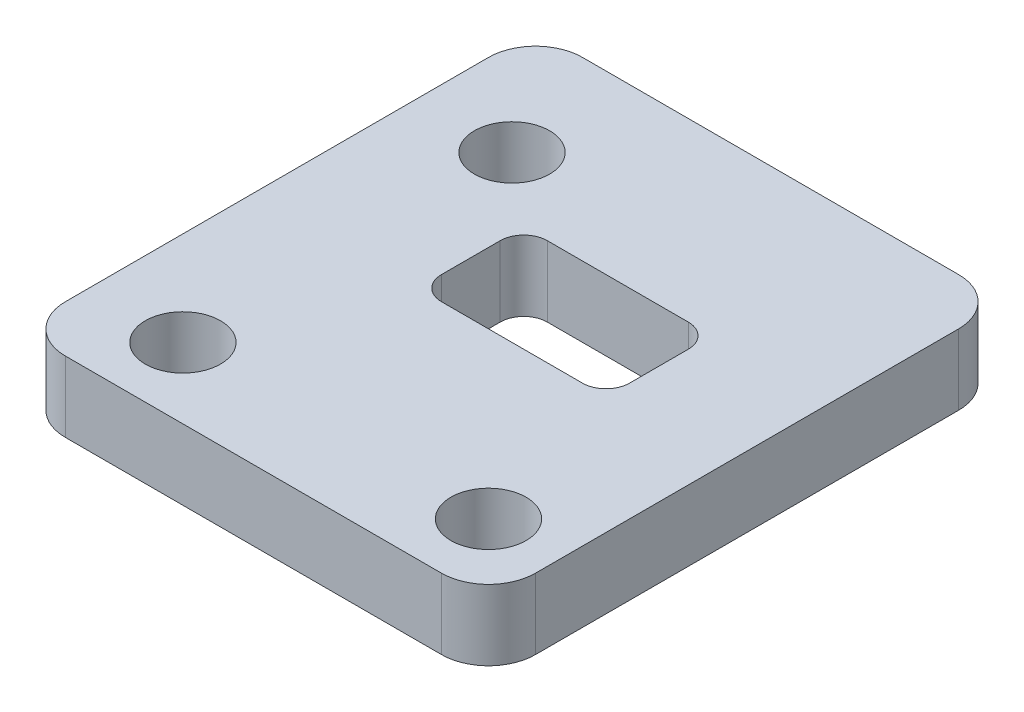
SolidWorks part; units mm, degrees
material "碳纤维"
ref_plane "前视基准面" through (0, 0, 0) normal (0, 0, 1) x (1, 0, 0)
ref_plane "上视基准面" through (0, 0, 0) normal (0, 1, 0) x (1, 0, 0)
ref_plane "右视基准面" through (0, 0, 0) normal (1, 0, 0) x (0, 0, -1)
sketch "草图2" plane through (0, 0, 0) normal (0, 1, 0) x (1, 0, 0)
  line L1 (-10, -10) -> (10, -10)
  line L2 (-10, -10) -> (-10, 10)
  line L3 (-10, 10) -> (10, 10) construction
  line L5 (0, 10) -> (0, -10) construction
  line L6 (-10, 0) -> (10, 0) construction
  line L11 (10, 10) -> (10, -10)
  line L12 (1, 0) -> (1, -10) construction
  line L20 (-3, 0) -> (5, 0)
  line L21 (-3, 0) -> (-3, 4.5)
  line L22 (-3, 4.5) -> (5, 4.5)
  line L23 (5, 0) -> (5, 4.5)
  line L25 (-10, 10) -> (10, 10) construction
  line L26 (-10, 10) -> (-10, 12)
  line L27 (-10, 12) -> (10, 12)
  line L28 (10, 10) -> (10, 12)
  line L29 (0, 12) -> (0, 10) construction
  line L30 (-10, 11) -> (10, 11) construction
  circle A0 centre (-6, 7) radius 1.6
  circle A1 centre (-6, -7) radius 1.6
  circle A2 centre (7, -7) radius 1.6
  point P175 (0, 11)
  dimension "D2" = 3.2
  dimension "D1" = 14
  dimension "D3" = 20
  dimension "D4" = 4
  dimension "D5" = 20
  dimension "D6" = 4.5
  dimension "D7" = 8
  dimension "D8" = 7
  dimension "D9" = 3
  dimension "D10" = 2
extrude "凸台-拉伸1" add sketch "草图2" along normal blind 3
fillet "圆角1" radius 2 4 edges at (10, 1.5, 10) (-10, 1.5, 10) (10, 1.5, -12) (-10, 1.5, -12)
fillet "圆角2" radius 1 4 edges at (5, 1.5, -4.5) (-3, 1.5, -4.5) (-3, 1.5, 0) (5, 1.5, 0)
